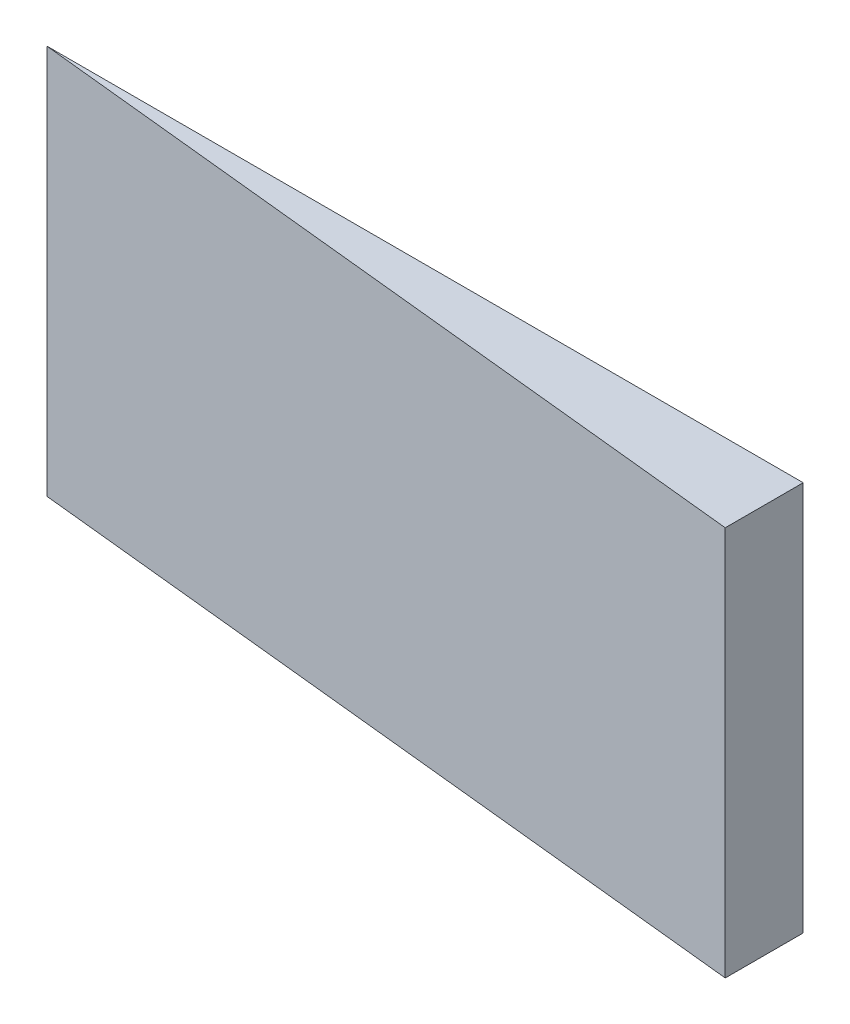
SolidWorks part; units mm, degrees
material "WhitePLA"
ref_plane "Front Plane" through (0, 0, 0) normal (0, 0, 1) x (1, 0, 0)
ref_plane "Top Plane" through (0, 0, 0) normal (0, 1, 0) x (1, 0, 0)
ref_plane "Right Plane" through (0, 0, 0) normal (1, 0, 0) x (0, 0, -1)
sketch "Sketch1" plane through (0, 0, 0) normal (0, 1, 0) x (1, 0, 0)
  line L0 (0, 0) -> (0, -5)
  line L1 (-48.5, 0) -> (0, 0)
  line L2 (-48.5, 0) -> (0, -5)
  dimension "D1" = 5
  dimension "D2" = 48.5
extrude "Boss-Extrude1" add sketch "Sketch1" along normal blind 25
